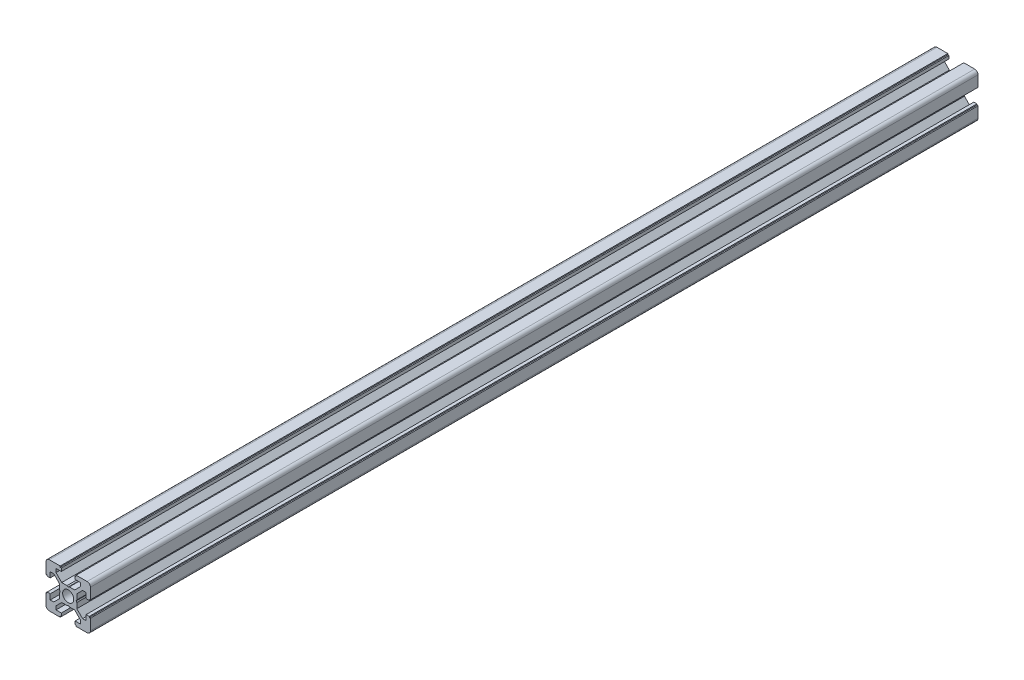
SolidWorks part; units mm, degrees
ref_plane "前视基准面" through (0, 0, 0) normal (0, 0, 1) x (1, 0, 0)
ref_plane "上视基准面" through (0, 0, 0) normal (0, 1, 0) x (1, 0, 0)
ref_plane "右视基准面" through (0, 0, 0) normal (1, 0, 0) x (0, 0, -1)
sketch "草图28" plane through (0, 0, 0) normal (0, 0, 1) x (1, 0, 0)
  line B0 (0, 11.0182) -> (0, -11.0182) construction
  line B1 (-11.0182, 0) -> (11.0182, 0) construction
  line B2 (-3.9, -0.5196) -> (-3.9, -2.9101)
  line B3 (-3.9, -2.9101) -> (-6.4899, -5.5)
  line B4 (-6.4899, -5.5) -> (-8.1, -5.5)
  line B5 (-8.1, -5.5) -> (-8.1, -3.1)
  line B6 (-8.1, -3.1) -> (-9.5, -3.1)
  line B7 (-9.5, -3.1) -> (-9.5, -3.6)
  line B8 (-9.5, -3.6) -> (-10, -3.6)
  line B9 (-10, -3.6) -> (-10, -8.5)
  line B10 (-8.5, -10) -> (-3.6, -10)
  line B11 (-3.6, -10) -> (-3.6, -9.5)
  line B12 (-3.6, -9.5) -> (-3.1, -9.5)
  line B13 (-3.1, -9.5) -> (-3.1, -8.1)
  line B14 (-3.1, -8.1) -> (-5.5, -8.1)
  line B15 (-5.5, -8.1) -> (-5.5, -6.4899)
  line B16 (-5.5, -6.4899) -> (-2.9101, -3.9)
  line B17 (-2.9101, -3.9) -> (-0.5196, -3.9)
  line B18 (-0.5196, -3.9) -> (0, -3.6)
  line B19 (0, -3.6) -> (0.5196, -3.9)
  line B20 (0.5196, -3.9) -> (2.9101, -3.9)
  line B21 (2.9101, -3.9) -> (5.5, -6.4899)
  line B22 (5.5, -6.4899) -> (5.5, -8.1)
  line B23 (5.5, -8.1) -> (3.1, -8.1)
  line B24 (3.1, -8.1) -> (3.1, -9.5)
  line B25 (3.1, -9.5) -> (3.6, -9.5)
  line B26 (3.6, -9.5) -> (3.6, -10)
  line B27 (3.6, -10) -> (8.5, -10)
  line B28 (10, -8.5) -> (10, -3.6)
  line B29 (10, -3.6) -> (9.5, -3.6)
  line B30 (9.5, -3.6) -> (9.5, -3.1)
  line B31 (9.5, -3.1) -> (8.1, -3.1)
  line B32 (8.1, -3.1) -> (8.1, -5.5)
  line B33 (8.1, -5.5) -> (6.4899, -5.5)
  line B34 (6.4899, -5.5) -> (3.9, -2.9101)
  line B35 (3.9, -2.9101) -> (3.9, -0.5196)
  line B36 (3.9, -0.5196) -> (3.6, 0)
  line B37 (3.6, 0) -> (3.9, 0.5196)
  line B38 (3.9, 0.5196) -> (3.9, 2.9101)
  line B39 (3.9, 2.9101) -> (6.4899, 5.5)
  line B40 (6.4899, 5.5) -> (8.1, 5.5)
  line B41 (8.1, 5.5) -> (8.1, 3.1)
  line B42 (8.1, 3.1) -> (9.5, 3.1)
  line B43 (9.5, 3.1) -> (9.5, 3.6)
  line B44 (9.5, 3.6) -> (10, 3.6)
  line B45 (10, 3.6) -> (10, 8.5)
  line B46 (8.5, 10) -> (3.6, 10)
  line B47 (3.6, 10) -> (3.6, 9.5)
  line B48 (3.6, 9.5) -> (3.1, 9.5)
  line B49 (3.1, 9.5) -> (3.1, 8.1)
  line B50 (3.1, 8.1) -> (5.5, 8.1)
  line B51 (5.5, 8.1) -> (5.5, 6.4899)
  line B52 (5.5, 6.4899) -> (2.9101, 3.9)
  line B53 (2.9101, 3.9) -> (0.5196, 3.9)
  line B54 (0.5196, 3.9) -> (0, 3.6)
  line B55 (0, 3.6) -> (-0.5196, 3.9)
  line B56 (-0.5196, 3.9) -> (-2.9101, 3.9)
  line B57 (-2.9101, 3.9) -> (-5.5, 6.4899)
  line B58 (-5.5, 6.4899) -> (-5.5, 8.1)
  line B59 (-5.5, 8.1) -> (-3.1, 8.1)
  line B60 (-3.1, 8.1) -> (-3.1, 9.5)
  line B61 (-3.1, 9.5) -> (-3.6, 9.5)
  line B62 (-3.6, 9.5) -> (-3.6, 10)
  line B63 (-3.6, 10) -> (-8.5, 10)
  line B64 (-10, 8.5) -> (-10, 3.6)
  line B65 (-10, 3.6) -> (-9.5, 3.6)
  line B66 (-9.5, 3.6) -> (-9.5, 3.1)
  line B67 (-9.5, 3.1) -> (-8.1, 3.1)
  line B68 (-8.1, 3.1) -> (-8.1, 5.5)
  line B69 (-8.1, 5.5) -> (-6.4899, 5.5)
  line B70 (-6.4899, 5.5) -> (-3.9, 2.9101)
  line B71 (-3.9, 2.9101) -> (-3.9, 0.5196)
  line B72 (-3.9, 0.5196) -> (-3.6, 0)
  line B73 (-3.6, 0) -> (-3.9, -0.5196)
  circle B74 centre (0, 0) radius 2.5
  arc B75 (-10, -8.5) -> (-8.5, -10) centre (-8.5, -8.5) ccw
  arc B76 (8.5, -10) -> (10, -8.5) centre (8.5, -8.5) ccw
  arc B77 (10, 8.5) -> (8.5, 10) centre (8.5, 8.5) ccw
  arc B78 (-8.5, 10) -> (-10, 8.5) centre (-8.5, 8.5) ccw
sketch_block_instance "块1-1"
sketch_block "块1"
extrude "凸台-拉伸1" add sketch "草图28" along normal blind 400
cosmetic thread "装饰螺纹线1" [suppressed] parameters "D1"=115, "D2"=6
cosmetic thread "装饰螺纹线2" [suppressed] parameters "D1"=15, "D2"=6
ref_plane "基准面1" through (0, 0, 400) normal (0, 0, 1) x (1, 0, 0)
ref_plane "基准面2" through (0, 10, 0) normal (0, 1, 0) x (1, 0, 0)
ref_plane "基准面3" through (0, -10, 0) normal (0, 1, 0) x (1, 0, 0)
ref_plane "基准面4" through (10, 0, 0) normal (1, 0, 0) x (0, 0, -1)
ref_plane "基准面5" through (-10, 0, 0) normal (1, 0, 0) x (0, 0, -1)
sketch "草图19" plane through (0, 0, 0) normal (0, 0, 1) x (1, 0, 0)
  line L0 (0, 0) -> (0, 11.6901) construction
  line L1 (0, 0) -> (10.3437, 0) construction
sketch "草图20" plane through (0, 0, 0) normal (0, 1, 0) x (1, 0, 0)
  line L0 (0, 0) -> (0, 3.5576) construction
ref_point "点1"
sketch "草图2" [suppressed] plane through (0, 0, 0) normal (1, 0, 0) x (0, 0, -1)
  line L0 (-280, -10) -> (-260, 10)
  line L1 (16.5, -10) -> (-16.5, -10) construction
  line L2 (16.5, 10) -> (-16.5, 10) construction
  line L3 (-260, 10) -> (-280, 10)
  line L4 (-280, 16.5) -> (-280, -16.5) construction
  line L5 (-280, 10) -> (-280, -10)
  dimension "D1" = 45
extrude "切除-拉伸1" [suppressed] cut sketch "草图2" against normal through all and the other way through all
sketch "草图3" [suppressed] plane through (0, 0, 0) normal (1, 0, 0) x (0, 0, -1)
  line L0 (0, -10) -> (-20, 10)
  line L1 (16.5, -10) -> (-16.5, -10) construction
  line L2 (16.5, 10) -> (-16.5, 10) construction
  line L3 (-20, 10) -> (0, 10)
  line L4 (0, 10) -> (0, -10)
  line L5 (0, 11) -> (0, -11) construction
  dimension "D1" = 45
extrude "切除-拉伸2" [suppressed] cut sketch "草图3" against normal through all and the other way through all
sketch "草图4" [suppressed] plane through (0, 0, 0) normal (1, 0, 0) x (0, 0, -1)
  line L0 (-280, 10) -> (-260, -10)
  line L1 (16.5, 10) -> (-16.5, 10) construction
  line L2 (-280, 16.5) -> (-280, -16.5) construction
  line L3 (16.5, -10) -> (-16.5, -10) construction
  line L4 (-260, -10) -> (-280, -10)
  line L5 (-280, -10) -> (-280, 10)
  dimension "D1" = 45
extrude "切除-拉伸3" [suppressed] cut sketch "草图4" against normal through all and the other way through all
sketch "草图5" [suppressed] plane through (0, 0, 0) normal (1, 0, 0) x (0, 0, -1)
  line L0 (0, 10) -> (-20, -10)
  line L1 (16.5, 10) -> (-16.5, 10) construction
  line L2 (16.5, -10) -> (-16.5, -10) construction
  line L3 (-20, -10) -> (0, -10)
  line L4 (0, -10) -> (0, 10)
  line L5 (0, 11) -> (0, -11) construction
  dimension "D1" = 45
extrude "切除-拉伸4" [suppressed] cut sketch "草图5" against normal through all and the other way through all
sketch "草图6" [suppressed] plane through (0, 0, 0) normal (0, 1, 0) x (1, 0, 0)
  line L0 (-10, -280) -> (10, -260)
  line L1 (-10, -16.5) -> (-10, 16.5) construction
  line L2 (-16.5, -280) -> (16.5, -280) construction
  line L3 (10, -16.5) -> (10, 16.5) construction
  line L4 (10, -260) -> (10, -280)
  line L5 (10, -280) -> (-10, -280)
  dimension "D1" = 45
extrude "切除-拉伸5" [suppressed] cut sketch "草图6" against normal through all and the other way through all
sketch "草图7" [suppressed] plane through (0, 0, 0) normal (0, 1, 0) x (1, 0, 0)
  line L0 (-10, 0) -> (10, -20)
  line L1 (-10, -16.5) -> (-10, 16.5) construction
  line L2 (10, -16.5) -> (10, 16.5) construction
  line L3 (10, -20) -> (10, 0)
  line L4 (-11, 0) -> (11, 0) construction
  line L5 (10, 0) -> (-10, 0)
  dimension "D1" = 45
extrude "切除-拉伸6" [suppressed] cut sketch "草图7" against normal through all and the other way through all
sketch "草图8" [suppressed] plane through (0, 0, 0) normal (0, 1, 0) x (1, 0, 0)
  line L0 (-10, -260) -> (10, -280)
  line L1 (-10, -16.5) -> (-10, 16.5) construction
  line L2 (10, -16.5) -> (10, 16.5) construction
  line L3 (-16.5, -280) -> (16.5, -280) construction
  line L4 (10, -280) -> (-10, -280)
  line L5 (-10, -280) -> (-10, -260)
  dimension "D1" = 45
extrude "切除-拉伸7" [suppressed] cut sketch "草图8" against normal through all and the other way through all
sketch "草图9" [suppressed] plane through (0, 0, 0) normal (0, 1, 0) x (1, 0, 0)
  line L0 (10, 0) -> (-10, -20)
  line L1 (10, -16.5) -> (10, 16.5) construction
  line L2 (-11, 0) -> (11, 0) construction
  line L3 (-10, -16.5) -> (-10, 16.5) construction
  line L4 (-10, -20) -> (-10, 0)
  line L5 (-10, 0) -> (10, 0)
  dimension "D1" = 45
extrude "切除-拉伸8" [suppressed] cut sketch "草图9" against normal through all and the other way through all
sketch "草图10" [suppressed] plane through (10, -3.64, 139.7) normal (1, 0, 0) x (0, 0, -1)
  line L1 (-140.3, 20.14) -> (-140.3, -12.86) construction
  circle A0 centre (-127.3, 3.64) radius 5
  dimension "D1" = 10
  dimension "D2" = 13
extrude "切除-拉伸9" [suppressed] cut sketch "草图10" against normal blind 9
sketch "草图11" [suppressed] plane through (10, 0, 0) normal (1, 0, 0) x (0, 0, -1)
  circle A0 centre (-13, 0) radius 5
  dimension "D1" = 10
  dimension "D2" = 13
extrude "切除-拉伸10" [suppressed] cut sketch "草图11" against normal blind 9
sketch "草图12" [suppressed] plane through (0, 0, 0) normal (0, 1, 0) x (1, 0, 0)
  line L0 (-10, -16.5) -> (-10, 16.5) construction
  line L1 (-10, -267) -> (-1, -267)
  line L2 (-10, -267) -> (-10, -262)
  line L3 (-10, -262) -> (-1, -262)
  line L4 (-1, -267) -> (-1, -262)
  line L5 (10, -16.5) -> (10, 16.5) construction
  line L6 (10, -267) -> (1, -267)
  line L7 (10, -267) -> (10, -262)
  line L8 (10, -262) -> (1, -262)
  line L9 (1, -267) -> (1, -262)
  line L10 (-16.5, -280) -> (16.5, -280) construction
  dimension "D1" = 13
  dimension "D2" = 5
  dimension "D3" = 9
revolve "切除-旋转1" [suppressed] cut sketch "草图12" angle 360 about L1
sketch "草图13" [suppressed] plane through (0, 0, 0) normal (0, 1, 0) x (1, 0, 0)
  line L0 (-10, -16.5) -> (-10, 16.5) construction
  line L1 (-10, -18) -> (-1, -18)
  line L2 (-10, -18) -> (-10, -13)
  line L3 (-10, -13) -> (-1, -13)
  line L4 (-1, -18) -> (-1, -13)
  line L5 (10, -16.5) -> (10, 16.5) construction
  line L6 (10, -18) -> (1, -18)
  line L7 (10, -18) -> (10, -13)
  line L8 (10, -13) -> (1, -13)
  line L9 (1, -18) -> (1, -13)
  dimension "D1" = 13
  dimension "D2" = 5
  dimension "D3" = 9
revolve "切除-旋转2" [suppressed] cut sketch "草图13" angle 360 about L3
sketch "草图14" [suppressed] plane through (0, 10, 0) normal (0, 1, 0) x (1, 0, 0)
  line L0 (-16.5, -280) -> (16.5, -280) construction
  circle A0 centre (0, -267) radius 5
  dimension "D1" = 10
  dimension "D2" = 13
extrude "切除-拉伸11" [suppressed] cut sketch "草图14" against normal blind 9
sketch "草图15" [suppressed] plane through (0, 10, 0) normal (0, 1, 0) x (1, 0, 0)
  line L0 (-11, 0) -> (11, 0) construction
  circle A0 centre (0, -13) radius 5
  dimension "D1" = 10
  dimension "D2" = 13
extrude "切除-拉伸12" [suppressed] cut sketch "草图15" against normal blind 9
sketch "草图16" [suppressed] plane through (0, 0, 0) normal (1, 0, 0) x (0, 0, -1)
  line L0 (16.5, 10) -> (-16.5, 10) construction
  line L1 (-267, 10) -> (-262, 10)
  line L2 (-267, 10) -> (-267, 1)
  line L3 (-267, 1) -> (-262, 1)
  line L4 (-262, 10) -> (-262, 1)
  line L5 (16.5, -10) -> (-16.5, -10) construction
  line L6 (-267, -10) -> (-262, -10)
  line L7 (-267, -10) -> (-267, -1)
  line L8 (-267, -1) -> (-262, -1)
  line L9 (-262, -10) -> (-262, -1)
  line L10 (-280, 16.5) -> (-280, -16.5) construction
  dimension "D1" = 9
  dimension "D2" = 5
  dimension "D3" = 13
revolve "切除-旋转3" [suppressed] cut sketch "草图16" angle 360 about L2
sketch "草图17" [suppressed] plane through (0, 0, 0) normal (1, 0, 0) x (0, 0, -1)
  line L0 (16.5, 10) -> (-16.5, 10) construction
  line L1 (-13, 10) -> (-18, 10)
  line L2 (-13, 10) -> (-13, 1)
  line L3 (-13, 1) -> (-18, 1)
  line L4 (-18, 10) -> (-18, 1)
  line L5 (16.5, -10) -> (-16.5, -10) construction
  line L6 (-13, -10) -> (-18, -10)
  line L7 (-13, -10) -> (-13, -1)
  line L8 (-13, -1) -> (-18, -1)
  line L9 (-18, -10) -> (-18, -1)
  dimension "D1" = 5
  dimension "D2" = 9
  dimension "D3" = 13
revolve "切除-旋转4" [suppressed] cut sketch "草图17" angle 360 about L2
sketch "草图18" [suppressed] plane through (0, 0, 0) normal (0, 1, 0) x (1, 0, 0)
  line L0 (-10, -230) -> (10, -230)
  line L1 (-10, -16.5) -> (-10, 16.5) construction
  line L2 (10, -16.5) -> (10, 16.5) construction
  line L3 (10, -230) -> (10, -224.5)
  line L4 (10, -224.5) -> (3.5, -224.5)
  line L5 (3.5, -224.5) -> (3.5, -226.75)
  line L6 (3.5, -226.75) -> (-10, -226.75)
  line L7 (-10, -226.75) -> (-10, -230)
  line L8 (-16.5, -280) -> (16.5, -280) construction
  dimension "D1" = 50
  dimension "D2" = 5.5
  dimension "D3" = 3.25
  dimension "D4" = 6.5
revolve "切除-旋转5" [suppressed] cut sketch "草图18" angle 360 about L0
other "表格阵列1" [suppressed] parameters "D0"=70, "D1"=0, "D2"=90, "D3"=0, "D4"=110, "D5"=0, "D6"=130, "D7"=0
sketch "草图21" [suppressed] plane through (0, 0, 0) normal (0, 1, 0) x (1, 0, 0)
  line L0 (-10, -50) -> (10, -50)
  line L1 (-10, -16.5) -> (-10, 16.5) construction
  line L2 (10, -16.5) -> (10, 16.5) construction
  line L3 (10, -50) -> (10, -55.5)
  line L4 (10, -55.5) -> (3.5, -55.5)
  line L5 (3.5, -55.5) -> (3.5, -53.25)
  line L6 (3.5, -53.25) -> (-10, -53.25)
  line L7 (-10, -53.25) -> (-10, -50)
  dimension "D1" = 5.5
  dimension "D2" = 3.25
  dimension "D3" = 6.5
  dimension "D4" = 50
revolve "切除-旋转6" [suppressed] cut sketch "草图21" angle 360 about L0
other "表格阵列2" [suppressed] parameters "D0"=70, "D1"=0, "D2"=90, "D3"=0, "D4"=110, "D5"=0, "D6"=130, "D7"=0
sketch "草图22" [suppressed] plane through (0, 0, 0) normal (1, 0, 0) x (0, 0, -1)
  line L0 (-230, 10) -> (-230, -10)
  line L1 (16.5, 10) -> (-16.5, 10) construction
  line L2 (16.5, -10) -> (-16.5, -10) construction
  line L3 (-230, -10) -> (-226.75, -10)
  line L4 (-226.75, -10) -> (-226.75, 3.5)
  line L5 (-226.75, 3.5) -> (-224.5, 3.5)
  line L6 (-224.5, 3.5) -> (-224.5, 10)
  line L7 (-224.5, 10) -> (-230, 10)
  line L8 (-280, 16.5) -> (-280, -16.5) construction
  dimension "D1" = 5.5
  dimension "D2" = 3.25
  dimension "D3" = 6.5
  dimension "D4" = 50
revolve "切除-旋转7" [suppressed] cut sketch "草图22" angle 360 about L0
other "表格阵列3" [suppressed] parameters "D0"=70, "D1"=0, "D2"=90, "D3"=0, "D4"=110, "D5"=0, "D6"=130, "D7"=0
sketch "草图23" [suppressed] plane through (0, 0, 0) normal (1, 0, 0) x (0, 0, -1)
  line L0 (-50, 10) -> (-55.5, 10)
  line L1 (16.5, 10) -> (-16.5, 10) construction
  line L2 (-55.5, 10) -> (-55.5, 3.5)
  line L3 (-55.5, 3.5) -> (-53.25, 3.5)
  line L4 (-53.25, 3.5) -> (-53.25, -10)
  line L5 (16.5, -10) -> (-16.5, -10) construction
  line L6 (-53.25, -10) -> (-50, -10)
  line L7 (-50, -10) -> (-50, 10)
  dimension "D1" = 5.5
  dimension "D2" = 3.25
  dimension "D3" = 6.5
  dimension "D4" = 50
revolve "切除-旋转8" [suppressed] cut sketch "草图23" angle 360 about L7
other "表格阵列4" [suppressed] parameters "D0"=70, "D1"=0, "D2"=90, "D3"=0, "D4"=110, "D5"=0, "D6"=130, "D7"=0
sketch "草图24" [suppressed] plane through (10, 0, 0) normal (1, 0, 0) x (0, 0, -1)
  line L0 (-280, 16.5) -> (-280, -16.5) construction
  circle A0 centre (-240, 0) radius 3.25
  dimension "D1" = 6.5
  dimension "D2" = 40
extrude "切除-拉伸13" [suppressed] cut sketch "草图24" against normal through all
other "表格阵列5" [suppressed] parameters "D0"=60, "D1"=0, "D2"=80, "D3"=0, "D4"=100, "D5"=0, "D6"=120, "D7"=0
sketch "草图25" [suppressed] plane through (10, 0, 0) normal (1, 0, 0) x (0, 0, -1)
  circle A0 centre (-40, 0) radius 3.25
  dimension "D1" = 6.5
  dimension "D2" = 40
extrude "切除-拉伸14" [suppressed] cut sketch "草图25" against normal through all
other "表格阵列6" [suppressed] parameters "D0"=60, "D1"=0, "D2"=80, "D3"=0, "D4"=100, "D5"=0, "D6"=120, "D7"=0
sketch "草图26" [suppressed] plane through (0, 10, 0) normal (0, 1, 0) x (1, 0, 0)
  line L0 (-16.5, -280) -> (16.5, -280) construction
  circle A0 centre (0, -240) radius 3.25
  dimension "D1" = 6.5
  dimension "D2" = 40
extrude "切除-拉伸15" [suppressed] cut sketch "草图26" against normal through all
other "表格阵列7" [suppressed] parameters "D0"=60, "D1"=0, "D2"=80, "D3"=0, "D4"=100, "D5"=0, "D6"=120, "D7"=0
sketch "草图27" [suppressed] plane through (0, 10, 0) normal (0, 1, 0) x (1, 0, 0)
  circle A0 centre (0, -40) radius 3.25
  dimension "D1" = 6.5
  dimension "D2" = 40
extrude "切除-拉伸16" [suppressed] cut sketch "草图27" against normal through all
other "表格阵列8" [suppressed] parameters "D0"=60, "D1"=0, "D2"=80, "D3"=0, "D4"=100, "D5"=0, "D6"=120, "D7"=0
